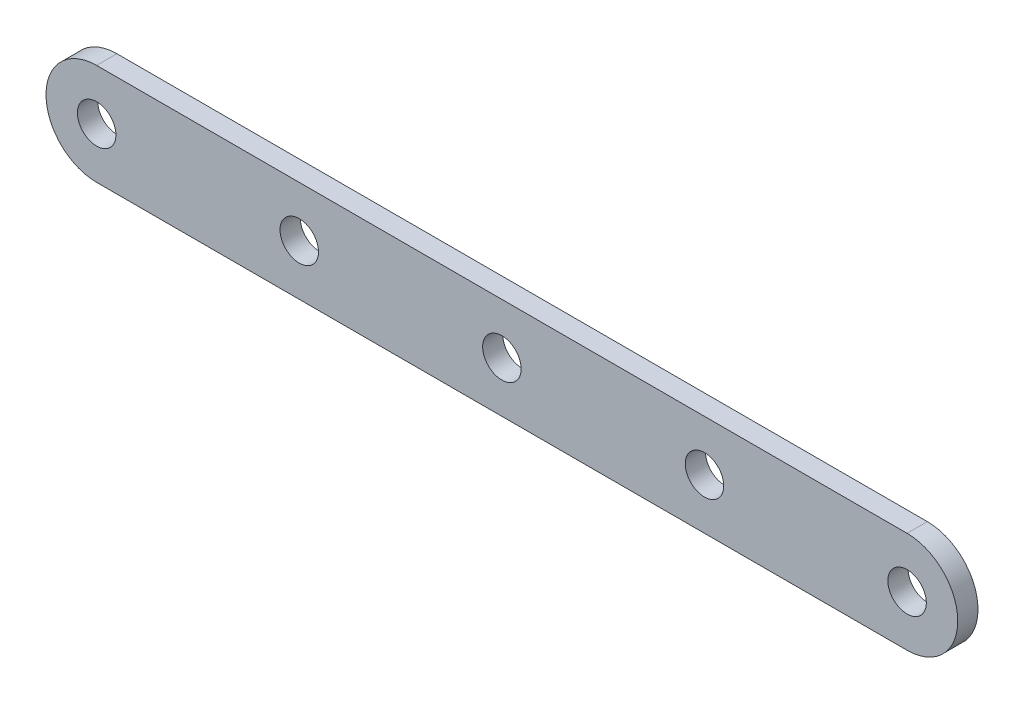
SolidWorks part; units mm, degrees
material "6061 Alloy"
ref_plane "Front Plane" through (0, 0, 0) normal (0, 0, 1) x (1, 0, 0)
ref_plane "Top Plane" through (0, 0, 0) normal (0, 1, 0) x (1, 0, 0)
ref_plane "Right Plane" through (0, 0, 0) normal (1, 0, 0) x (0, 0, -1)
sketch "Croquis1" plane through (0, 0, 0) normal (0, 0, 1) x (1, 0, 0)
  line L1 (48.26, -12.1612) -> (-53.34, -12.1612)
  line L3 (48.26, 0.5388) -> (-53.34, 0.5388)
  arc A0 (-53.34, 0.5388) -> (-53.34, -12.1612) centre (-53.34, -5.8112) ccw
  arc A1 (48.26, 0.5388) -> (48.26, -12.1612) centre (48.26, -5.8112) cw
  point P0 (0, 0)
  dimension "D2" = 6.35
  dimension "D1" = 101.6
extrude "Saliente-Extruir1" add sketch "Croquis1" along normal mid plane 2.54
sketch "Croquis2" plane through (0, 0, 1.27) normal (0, 0, 1) x (1, 0, 0)
  circle A0 centre (-53.34, -5.8112) radius 2.413
  dimension "D1" = 4.826
extrude "Cortar-Extruir1" cut sketch "Croquis2" against normal through all
pattern_linear "MatrizL2" count 5 spacing 25.4 along (1, 0, 0) of "Cortar-Extruir1"
